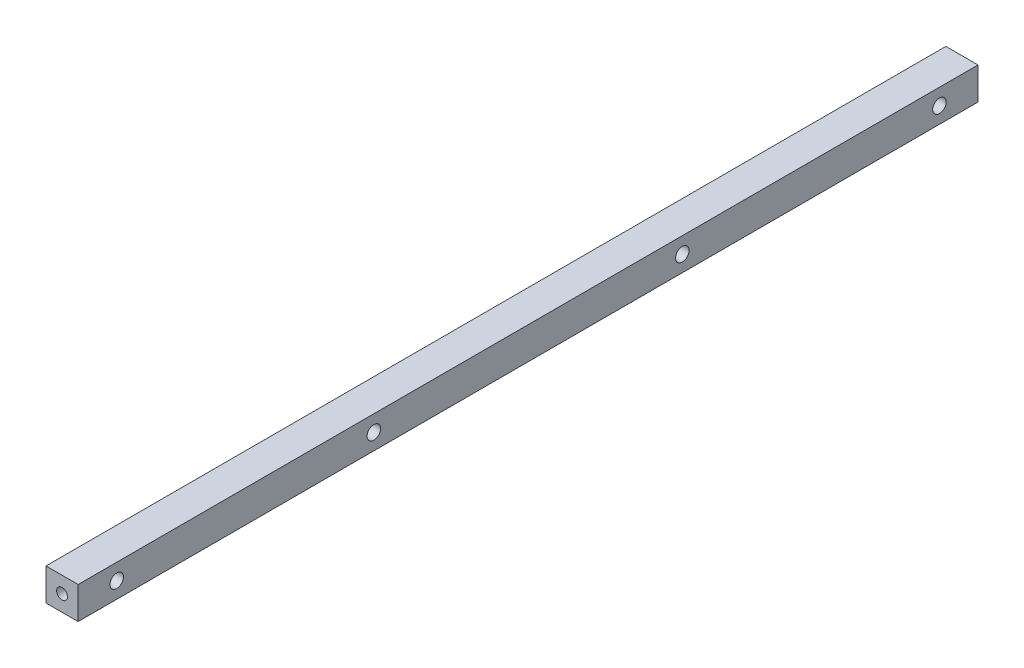
SolidWorks part; units mm, degrees
ref_plane "Спереди" through (0, 0, 0) normal (0, 0, 1) x (1, 0, 0)
ref_plane "Сверху" through (0, 0, 0) normal (0, 1, 0) x (1, 0, 0)
ref_plane "Справа" through (0, 0, 0) normal (1, 0, 0) x (0, 0, -1)
sketch "Эскиз1" plane through (0, 0, 0) normal (0, 0, 1) x (1, 0, 0)
  line L1 (0, 0) -> (25, 0)
  line L2 (0, 0) -> (0, 25)
  line L3 (0, 25) -> (25, 25)
  line L4 (25, 0) -> (25, 25)
  dimension "D1" = 25
  dimension "D2" = 25
extrude "Бобышка-Вытянуть1" add sketch "Эскиз1" along normal blind 700
sketch "Эскиз2" plane through (0, 0, 0) normal (-1, 0, 0) x (0, 0, 1)
  line L0 (40, 0) -> (40, 25) construction
  line L1 (700, 0) -> (0, 0) construction
  line L2 (700, 25) -> (0, 25) construction
  line L3 (0, 25) -> (0, 0) construction
  line L4 (48.4, 0) -> (51.6, 0)
  line L5 (48.4, 0) -> (48.4, 10)
  line L6 (48.4, 10) -> (51.6, 10)
  line L7 (51.6, 0) -> (51.6, 10)
  line L8 (98.4, 0) -> (98.4, 10)
  line L9 (98.4, 0) -> (101.6, 0)
  line L10 (101.6, 0) -> (101.6, 10)
  line L11 (98.4, 10) -> (101.6, 10)
  line L12 (148.4, 0) -> (148.4, 10)
  line L13 (148.4, 0) -> (151.6, 0)
  line L14 (151.6, 0) -> (151.6, 10)
  line L15 (148.4, 10) -> (151.6, 10)
  line L16 (198.4, 0) -> (198.4, 10)
  line L17 (198.4, 0) -> (201.6, 0)
  line L18 (201.6, 0) -> (201.6, 10)
  line L19 (198.4, 10) -> (201.6, 10)
  line L20 (248.4, 0) -> (248.4, 10)
  line L21 (248.4, 0) -> (251.6, 0)
  line L22 (251.6, 0) -> (251.6, 10)
  line L23 (248.4, 10) -> (251.6, 10)
  line L24 (298.4, 0) -> (298.4, 10)
  line L25 (298.4, 0) -> (301.6, 0)
  line L26 (301.6, 0) -> (301.6, 10)
  line L27 (298.4, 10) -> (301.6, 10)
  line L28 (348.4, 0) -> (348.4, 10)
  line L29 (348.4, 0) -> (351.6, 0)
  line L30 (351.6, 0) -> (351.6, 10)
  line L31 (348.4, 10) -> (351.6, 10)
  line L32 (398.4, 0) -> (398.4, 10)
  line L33 (398.4, 0) -> (401.6, 0)
  line L34 (401.6, 0) -> (401.6, 10)
  line L35 (398.4, 10) -> (401.6, 10)
  line L36 (448.4, 0) -> (448.4, 10)
  line L37 (448.4, 0) -> (451.6, 0)
  line L38 (451.6, 0) -> (451.6, 10)
  line L39 (448.4, 10) -> (451.6, 10)
  line L40 (498.4, 0) -> (498.4, 10)
  line L41 (498.4, 0) -> (501.6, 0)
  line L42 (501.6, 0) -> (501.6, 10)
  line L43 (498.4, 10) -> (501.6, 10)
  line L44 (548.4, 0) -> (548.4, 10)
  line L45 (548.4, 0) -> (551.6, 0)
  line L46 (551.6, 0) -> (551.6, 10)
  line L47 (548.4, 10) -> (551.6, 10)
  line L48 (598.4, 0) -> (598.4, 10)
  line L49 (598.4, 0) -> (601.6, 0)
  line L50 (601.6, 0) -> (601.6, 10)
  line L51 (598.4, 10) -> (601.6, 10)
  line L52 (648.4, 0) -> (648.4, 10)
  line L53 (648.4, 0) -> (651.6, 0)
  line L54 (651.6, 0) -> (651.6, 10)
  line L55 (648.4, 10) -> (651.6, 10)
  line L56 (50, 10) -> (50, 25) construction
  dimension "D1" = 10
  dimension "D2" = 3.2
  dimension "D3" = 50
  dimension "D4" = 40
  dimension "D6" = 50
  dimension "D5" = 13
extrude "Вырез-Вытянуть1" cut sketch "Эскиз2" against normal blind 10
sketch "Эскиз3" plane through (0, 0, 0) normal (-1, 0, 0) x (0, 0, 1)
  line L0 (0, 12.5) -> (700, 12.5) construction
  line L2 (0, 25) -> (0, 0) construction
  line L3 (700, 25) -> (700, 0) construction
  circle A0 centre (30, 12.5) radius 5.25
  circle A1 centre (670, 12.5) radius 5.25
  circle A2 centre (230, 12.5) radius 5.25
  circle A3 centre (470, 12.5) radius 5.25
  dimension "D1" = 10.5
  dimension "D2" = 10.5
  dimension "D3" = 30
  dimension "D4" = 30
  dimension "D5" = 10.5
  dimension "D6" = 10.5
  dimension "D7" = 200
  dimension "D8" = 200
extrude "Вырез-Вытянуть2" cut sketch "Эскиз3" against normal through all
sketch "Эскиз4" plane through (0, 0, 0) normal (0, 0, -1) x (-1, 0, 0)
  line L0 (0, 25) -> (-25, 0) construction
  line L2 (-25, 25) -> (0, 0) construction
  circle A0 centre (-12.5, 12.5) radius 4.25
  dimension "D1" = 8.5
extrude "Вырез-Вытянуть3" cut sketch "Эскиз4" against normal blind 30
cosmetic thread "Условное изображение резьбы2" parameters "D2"=10
sketch "Эскиз5" plane through (0, 0, 700) normal (0, 0, 1) x (1, 0, 0)
  line L0 (0, 25) -> (25, 0) construction
  line L1 (0, 0) -> (25, 25) construction
  circle A0 centre (12.5, 12.5) radius 4.25
  dimension "D1" = 8.5
extrude "Вырез-Вытянуть4" cut sketch "Эскиз5" against normal blind 30
cosmetic thread "Условное изображение резьбы1" parameters "D2"=10
